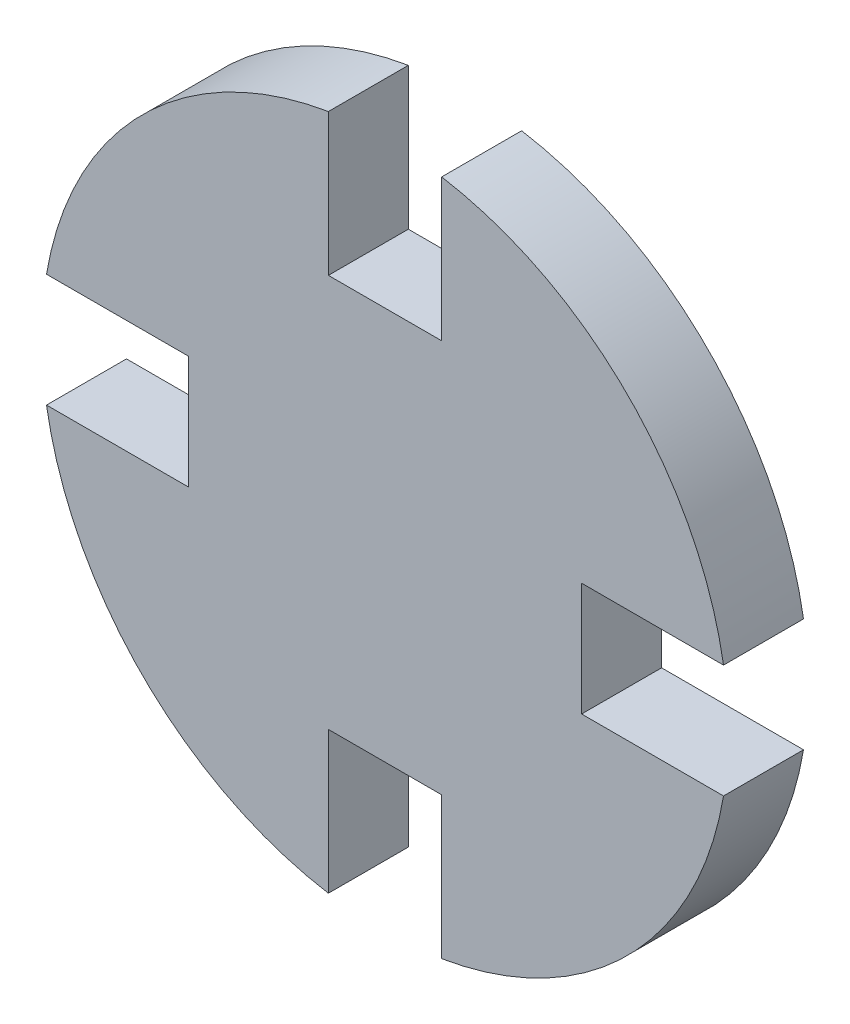
SolidWorks part; units mm, degrees
ref_plane "Front Plane" through (0, 0, 0) normal (0, 0, 1) x (1, 0, 0)
ref_plane "Top Plane" through (0, 0, 0) normal (0, 1, 0) x (1, 0, 0)
ref_plane "Right Plane" through (0, 0, 0) normal (1, 0, 0) x (0, 0, -1)
sketch "Sketch1" plane through (0, 0, 0) normal (0, 0, 1) x (1, 0, 0)
  line L0 (-25.3969, 4.25) -> (-14.75, 4.25)
  line L1 (-14.75, 4.25) -> (-14.75, -4.25)
  line L2 (-14.75, -4.25) -> (-25.3969, -4.25)
  line L3 (-4.25, -25.3969) -> (-4.25, -14.75)
  line L4 (-4.25, -14.75) -> (4.25, -14.75)
  line L5 (4.25, -14.75) -> (4.25, -25.3969)
  line L6 (25.3969, -4.25) -> (14.75, -4.25)
  line L7 (14.75, -4.25) -> (14.75, 4.25)
  line L8 (14.75, 4.25) -> (25.3969, 4.25)
  line L9 (4.25, 25.3969) -> (4.25, 14.75)
  line L10 (4.25, 14.75) -> (-4.25, 14.75)
  line L11 (-4.25, 14.75) -> (-4.25, 25.3969)
  line L12 (-25.6905, 4) -> (-15, 4) construction
  line L13 (-15, 4) -> (-15, -4) construction
  line L14 (-15, -4) -> (-25.6905, -4) construction
  line L15 (-4, -25.6905) -> (-4, -15) construction
  line L16 (-4, -15) -> (4, -15) construction
  line L17 (4, -15) -> (4, -25.6905) construction
  line L18 (25.6905, -4) -> (15, -4) construction
  line L19 (15, -4) -> (15, 4) construction
  line L20 (15, 4) -> (25.6905, 4) construction
  line L21 (4, 25.6905) -> (4, 15) construction
  line L22 (4, 15) -> (-4, 15) construction
  line L23 (-4, 15) -> (-4, 25.6905) construction
  arc A0 (-25.3969, -4.25) -> (-4.25, -25.3969) centre (0, 0) ccw
  arc A1 (4.25, -25.3969) -> (25.3969, -4.25) centre (0, 0) ccw
  arc A2 (25.3969, 4.25) -> (4.25, 25.3969) centre (0, 0) ccw
  arc A3 (-4.25, 25.3969) -> (-25.3969, 4.25) centre (0, 0) ccw
  arc A4 (-25.6905, -4) -> (-4, -25.6905) centre (0, 0) ccw construction
  arc A5 (4, -25.6905) -> (25.6905, -4) centre (0, 0) ccw construction
  arc A6 (25.6905, 4) -> (4, 25.6905) centre (0, 0) ccw construction
  arc A7 (-4, 25.6905) -> (-25.6905, 4) centre (0, 0) ccw construction
  circle A8 centre (0, 0) radius 5.1
sketch "Sketch2" plane through (0, 0, 0) normal (0, 0, 1) x (1, 0, 0)
  line L0 (-25.3969, 4.25) -> (-14.75, 4.25) construction
  line L1 (-14.75, 4.25) -> (-14.75, -4.25) construction
  line L2 (-14.75, -4.25) -> (-25.3969, -4.25) construction
  line L3 (-4.25, -25.3969) -> (-4.25, -14.75) construction
  line L4 (-4.25, -14.75) -> (4.25, -14.75) construction
  line L5 (4.25, -14.75) -> (4.25, -25.3969) construction
  line L6 (25.3969, -4.25) -> (14.75, -4.25) construction
  line L7 (14.75, -4.25) -> (14.75, 4.25) construction
  line L8 (14.75, 4.25) -> (25.3969, 4.25) construction
  line L9 (4.25, 25.3969) -> (4.25, 14.75) construction
  line L10 (4.25, 14.75) -> (-4.25, 14.75) construction
  line L11 (-4.25, 14.75) -> (-4.25, 25.3969) construction
  line L12 (-25.3969, 4.25) -> (-14.75, 4.25)
  line L13 (-14.75, 4.25) -> (-14.75, -4.25)
  line L14 (-14.75, -4.25) -> (-25.3969, -4.25)
  line L15 (-4.25, -25.3969) -> (-4.25, -14.75)
  line L16 (-4.25, -14.75) -> (4.25, -14.75)
  line L17 (4.25, -14.75) -> (4.25, -25.3969)
  line L18 (25.3969, -4.25) -> (14.75, -4.25)
  line L19 (14.75, -4.25) -> (14.75, 4.25)
  line L20 (14.75, 4.25) -> (25.3969, 4.25)
  line L21 (4.25, 25.3969) -> (4.25, 14.75)
  line L22 (4.25, 14.75) -> (-4.25, 14.75)
  line L23 (-4.25, 14.75) -> (-4.25, 25.3969)
  arc A0 (-4.25, 25.3969) -> (-25.3969, 4.25) centre (0, 0) ccw construction
  arc A1 (-25.3969, -4.25) -> (-4.25, -25.3969) centre (0, 0) ccw construction
  arc A2 (4.25, -25.3969) -> (25.3969, -4.25) centre (0, 0) ccw construction
  arc A3 (25.3969, 4.25) -> (4.25, 25.3969) centre (0, 0) ccw construction
  arc A4 (-4.25, 25.3969) -> (-25.3969, 4.25) centre (0, 0) ccw
  arc A5 (-25.3969, -4.25) -> (-4.25, -25.3969) centre (0, 0) ccw
  arc A6 (4.25, -25.3969) -> (25.3969, -4.25) centre (0, 0) ccw
  arc A7 (25.3969, 4.25) -> (4.25, 25.3969) centre (0, 0) ccw
extrude "Boss-Extrude1" add sketch "Sketch2" along normal mid plane 6
sketch "Sketch3" plane through (0, 0, -3) normal (0, 0, -1) x (-1, 0, 0)
  circle A0 centre (0, 0) radius 5.1 construction
  circle A1 centre (0, 0) radius 5.1
extrude "Cut-Extrude1" cut sketch "Sketch3" against normal blind 2.5
